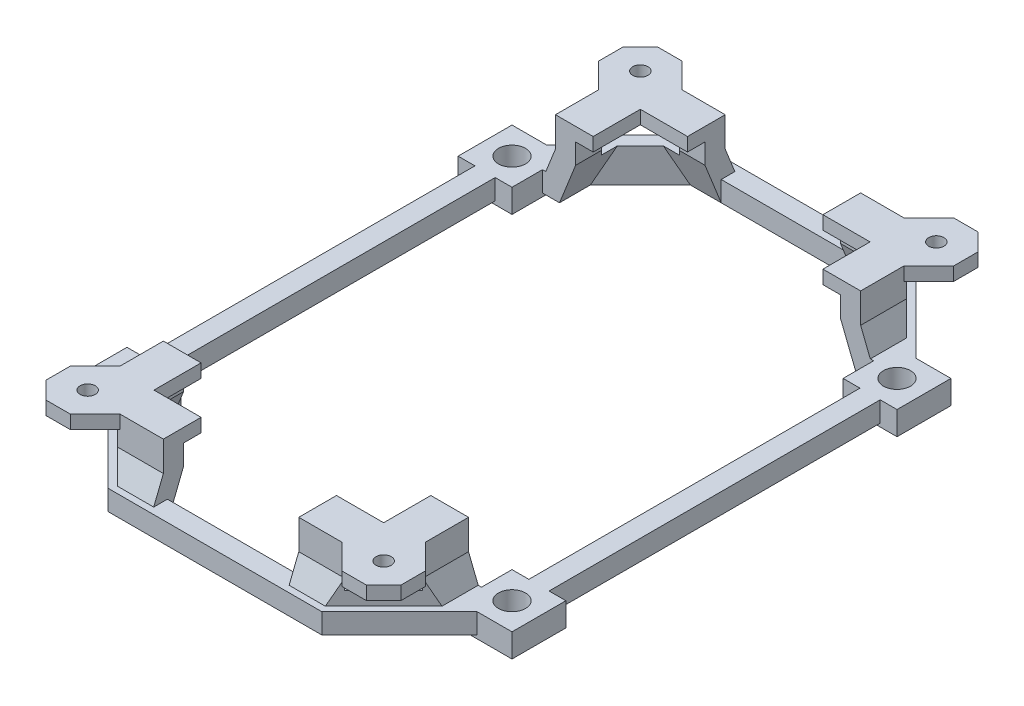
SolidWorks part; units mm, degrees
ref_plane "Front Plane" through (0, 0, 0) normal (0, 0, 1) x (1, 0, 0)
ref_plane "Top Plane" through (0, 0, 0) normal (0, 1, 0) x (1, 0, 0)
ref_plane "Right Plane" through (0, 0, 0) normal (1, 0, 0) x (0, 0, -1)
sketch "Sketch1" plane through (0, 0, 0) normal (0, 1, 0) x (1, 0, 0)
  line L0 (-54.15, 0) -> (-60.15, 0)
  line L1 (-60.15, 0) -> (-60.15, -49.15)
  line L2 (-60.15, -49.15) -> (-65.15, -49.15)
  line L3 (-65.15, -49.15) -> (-65.15, -65.15)
  line L4 (-65.15, -65.15) -> (-54.8069, -65.15)
  line L6 (-54.8069, -65.15) -> (-31.7569, -88.2)
  line L17 (-54.15, 0) -> (-54.15, -49.15)
  line L18 (-54.15, -49.15) -> (-49.15, -49.15)
  line L19 (-49.15, -49.15) -> (-49.15, -58.2)
  line L24 (-54.15, 0) -> (0, 0) construction
  line L25 (0, 0) -> (0, -92.25) construction
  line L26 (-39.3, -58.2) -> (-38.1, -58.2) construction
  line L27 (-38.1, 0) -> (-38.1, -76.2) construction
  line L28 (-65.15, -57.15) -> (-49.15, -57.15) construction
  line L29 (-38.1, -76.2) -> (0, -76.2) construction
  line L37 (-38.1, -76.2) -> (-39.3, -77.4) construction
  line L38 (-39.3, -77.4) -> (-39.3, -58.2) construction
  line L39 (-49.15, -58.2) -> (-39.3, -58.2)
  line L41 (-39.3, -77.4) -> (-20.1, -77.4) construction
  line L42 (-20.1, -77.4) -> (-20.1, -82.2)
  line L44 (-31.7569, -88.2) -> (0, -88.2)
  line L45 (0, -88.2) -> (0, -82.2)
  line L46 (0, -82.2) -> (-20.1, -82.2)
  line L47 (-39.3, -58.2) -> (-39.3, -69.3431)
  line L49 (-31.2431, -77.4) -> (-20.1, -77.4)
  line L50 (-20.1, -77.4) -> (-20.1, -76.2) construction
  line L51 (-39.3, -69.3431) -> (-31.2431, -77.4)
  point P37 (-57.15, 0)
  dimension "D1" = 6
  dimension "D2" = 16
  dimension "D4" = 57.15
  dimension "D5" = 57.15
  dimension "D6" = 76.2
  dimension "D7" = 38.1
  dimension "D8" = 45
  dimension "D10" = 6
  dimension "D9" = 18
  dimension "D3" = 1.2
  dimension "D11" = 135
  dimension "D12" = 4
  dimension "D13" = 4
extrude "Boss-Extrude1" add sketch "Sketch1" along normal blind 6
sketch "Sketch2" plane through (0, 0, 0) normal (0, -1, 0) x (1, 0, 0)
  line L0 (-49.15, 58.2) -> (-49.15, 49.15) construction
  line L1 (-65.15, 49.15) -> (-65.15, 65.15) construction
  line L2 (-49.15, 58.2) -> (-49.15, 49.15)
  line L3 (-65.15, 49.15) -> (-65.15, 65.15)
  line L5 (-65.15, 49.15) -> (-49.15, 49.15)
  line L6 (-65.15, 65.15) -> (-49.15, 65.15)
  line L7 (-49.15, 65.15) -> (-49.15, 58.2)
extrude "Boss-Extrude2" add sketch "Sketch2" along normal blind 1
sketch "Sketch3" plane through (0, 6, 0) normal (0, 1, 0) x (1, 0, 0)
  line L4 (-39.3, -58.2) -> (-45.3, -58.2)
  line L6 (-45.3, -58.2) -> (-45.3, -71.8284)
  line L9 (-20.1, -83.4) -> (-20.1, -77.4)
  line L10 (-45.3, -71.8284) -> (-33.7284, -83.4)
  line L11 (-33.7284, -83.4) -> (-20.1, -83.4)
  line L12 (-54.8069, -65.15) -> (-31.7569, -88.2) construction
  line L13 (-39.3, -58.2) -> (-39.3, -69.3431)
  line L14 (-39.3, -69.3431) -> (-31.2431, -77.4)
  line L15 (-31.2431, -77.4) -> (-20.1, -77.4)
  line L16 (-20.1, -77.4) -> (-31.2431, -77.4) construction
  line L17 (-39.3, -69.3431) -> (-39.3, -58.2) construction
  line L18 (-39.3, -58.2) -> (-49.15, -58.2) construction
  line L19 (-20.1, -82.2) -> (-20.1, -77.4) construction
  line L20 (-39.3, -69.3431) -> (-43.5426, -73.5858) construction
  line L21 (-39.3, -69.3431) -> (-45.3, -69.3431) construction
  dimension "D1" = 6
extrude "Boss-Extrude3" add sketch "Sketch3" along normal blind 12.05
sketch "Sketch4" plane through (0, 18.05, 0) normal (0, 1, 0) x (1, 0, 0)
  line L0 (-45.3, -58.2) -> (-34.1, -58.2)
  line L1 (-34.1, -58.2) -> (-34.1, -72.2)
  line L2 (-34.1, -72.2) -> (-20.1, -72.2)
  line L3 (-20.1, -72.2) -> (-20.1, -83.4)
  line L4 (-20.1, -83.4) -> (-32.9256, -83.4)
  line L5 (-33.7284, -83.4) -> (-20.1, -83.4) construction
  line L6 (-32.9256, -83.4) -> (-40.3093, -90.7836)
  line L7 (-40.3093, -90.7836) -> (-47.558, -90.7836)
  line L8 (-47.558, -90.7836) -> (-52.6836, -85.658)
  line L9 (-52.6836, -85.658) -> (-52.6836, -78.4093)
  line L10 (-52.6836, -78.4093) -> (-45.3, -71.0256)
  line L11 (-45.3, -71.0256) -> (-45.3, -58.2)
  line L12 (-43.9336, -82.0336) -> (-50.1208, -88.2208) construction
  line L13 (-43.9336, -82.0336) -> (-52.6836, -82.0336) construction
  line L14 (-42.3426, -80.4426) -> (-39.5142, -77.6142) construction
  line L15 (-45.3, -71.8284) -> (-33.7284, -83.4) construction
  line L16 (-51.7118, -77.4374) -> (-39.3374, -89.8118) construction
  circle A0 centre (-43.9336, -82.0336) radius 2.25
  dimension "D4" = 4.5
  dimension "D1" = 11.2
  dimension "D2" = 135
  dimension "D3" = 135
  dimension "D6" = 4
  dimension "D5" = 6.5
extrude "Boss-Extrude4" add sketch "Sketch4" along normal blind 4
sketch "Sketch5" plane through (-58.5642, 0, 58.5642) normal (-0.7071, 0, 0.7071) x (0.7071, 0, 0.7071)
  line L0 (18.7584, 18.05) -> (18.7584, 6) construction
  line L1 (18.7584, 18.05) -> (35.1231, 18.05)
  line L2 (18.7584, 18.05) -> (18.7584, 10.05)
  line L3 (18.7584, 10.05) -> (35.1231, 10.05)
  line L4 (35.1231, 18.05) -> (35.1231, 10.05)
  line L5 (35.1231, 18.05) -> (35.1231, 6) construction
  line L6 (18.7584, 18.05) -> (35.1231, 18.05) construction
  dimension "D1" = 8
extrude "Cut-Extrude1" cut sketch "Sketch5" against normal up to next and the other way through all
sketch "Sketch7" plane through (0, 0, 0) normal (0, -1, 0) x (1, 0, 0)
  line L0 (-31.7569, 88.2) -> (-29.2716, 82.2) construction
  line L1 (-29.449, 82.0226) -> (-34.9685, 76.5031) construction
  line L2 (-29.2716, 82.2) -> (0, 82.2) construction
  line L3 (0, 82.2) -> (-20.1, 82.2) construction
  line L4 (-54.8069, 65.15) -> (-31.7569, 88.2) construction
  line L5 (-31.7569, 88.2) -> (0, 88.2) construction
  point P7 (0, 0)
  point P14 (0, 0)
  point P15 (0, 0)
sketch "Sketch6" plane through (-20.1, 0, 0) normal (1, 0, 0) x (0, 0, -1)
  line L1 (-82.2, 0) -> (-77.4, 12.05)
  line L2 (-77.4, 18.05) -> (-77.4, 0) construction
  line L3 (-77.4, 12.05) -> (-77.4, 0)
  line L5 (-77.4, 18.05) -> (-72.2, 18.05) construction
  line L8 (-82.2, 0) -> (-77.4, 0)
  dimension "D1" = 6
extrude "Cut-Extrude2" cut sketch "Sketch6" against normal up to vertex (9.1716 mm away) up to point (-29.2716, 0, 82.2)
ref_plane "Plane1" through (19.05, 0, 19.05) normal (0.7071, 0, 0.7071) x (0.7071, 0, -0.7071)
mirror "Mirror1" about plane through (19.05, 0, 19.05) normal (0.7071, 0, 0.7071) of "Cut-Extrude2"
sketch "Sketch8" plane through (19.05, 0, 19.05) normal (0.7071, 0, 0.7071) x (0.7071, 0, -0.7071)
  line L8 (-78.8223, 0) -> (-78.8223, 10.05)
  line L9 (-78.8223, 10.05) -> (-75.4282, 10.05)
  line L10 (-75.4282, 10.05) -> (-75.4282, 0)
  line L11 (-75.4282, 0) -> (-78.8223, 0)
  line L12 (-75.4282, 0) -> (-75.4282, 10.05) construction
  line L13 (-75.9915, 10.05) -> (-75.4282, 10.05) construction
  point P2 (0, 0)
  point P13 (-76.5193, 8.407)
  point P14 (-75.6586, 9.5342)
  point P15 (-75.8629, 9.3632)
  point P16 (-76.7419, 8.2772)
  point P17 (0, 0)
extrude "Cut-Extrude3" cut sketch "Sketch8" against normal up to surface and the other way up to surface up to face at (-41.1656, 7.3667, 63.9328) other way up to face at (-25.8328, 7.3667, 79.2656)
sketch "Sketch10" plane through (-20.1, 0, 0) normal (1, 0, 0) x (0, 0, -1)
  line L0 (-83.4, 13.201) -> (-86.2685, 6)
  line L1 (-86.2685, 6) -> (-83.4, 6)
  line L2 (-83.4, 6) -> (-83.4, 13.201)
  line L3 (-83.4, 22.05) -> (-83.4, 6) construction
  line L4 (-88.2, 6) -> (-82.2, 6) construction
  line L5 (-77.4, 12.05) -> (-82.2, 0) construction
  line L6 (-78.1967, 10.05) -> (-82.2, 0) construction
  dimension "D1" = 6
extrude "Boss-Extrude5" add sketch "Sketch10" against normal up to vertex (13.6284 mm away)
sketch "Sketch11" plane through (19.05, 0, 19.05) normal (0.7071, 0, 0.7071) x (0.7071, 0, -0.7071)
  line L0 (-82.8223, 13.201) -> (-84.8506, 6)
  line L1 (-84.8506, 6) -> (-82.8223, 6)
  line L2 (-82.8223, 6) -> (-82.8223, 13.201)
  line L3 (-82.8223, 10.05) -> (-82.8223, 6) construction
  line L4 (-84.8223, 6) -> (-82.8223, 6) construction
  line L5 (-82.8223, 13.201) -> (-84.8506, 6) construction
extrude "Cut-Extrude4" cut sketch "Sketch11" along normal through all
mirror "Mirror2" about plane through (19.05, 0, 19.05) normal (0.7071, 0, 0.7071) of "Cut-Extrude4", "Boss-Extrude5"
sketch "Sketch12" plane through (0, 6, 0) normal (0, 1, 0) x (1, 0, 0)
  line L0 (-65.15, -65.15) -> (-49.15, -49.15) construction
  circle A0 centre (-57.15, -57.15) radius 4.0132
  point P6 (0, 0)
  point P7 (-57.15, -57.15)
  dimension "D1" = 8.0264
extrude "Cut-Extrude5" cut sketch "Sketch12" against normal through all
mirror "Mirror3" about plane through (-54.15, 6, 0) normal (0, 0, 1) of bodies 112
mirror "Mirror4" about plane through (0, 6, -88.2) normal (-1, 0, 0) of bodies 113
equation "\"sample_clearance\"= 1.2'sample to edge wall"
equation "\"truss_width\"= 6'thickness"
equation "\"truss_height\"= 6'thickness"
equation "\"truss_offset\"= 1'height offset from baseplate"
equation "\"D1@Sketch1\"=\"truss_width\""
equation "\"screw_spacing_short\"= 4.5in'baseplate spacing parallel to sample short side"
equation "\"screw_spacing_long\"= 4.5in'baseplate spacing parallel to sample long side"
equation "\"truss_bore_width\"= 16'box around bore hole"
equation "\"D2@Sketch1\"=\"truss_bore_width\""
equation "\"D4@Sketch1\"=\"screw_spacing_long\"/2"
equation "\"D5@Sketch1\"=\"screw_spacing_short\"/2"
equation "\"sample_long\"= 6in"
equation "\"sample_short\"= 3in"
equation "\"D6@Sketch1\"=\"sample_long\"/2"
equation "\"D7@Sketch1\"=\"sample_short\"/2"
equation "\"base_clearance_corner\"= 2"
equation "\"wall\"= 12"
equation "\"sample_short_to_truss\"= 6"
equation "\"D10@Sketch1\"=\"sample_short_to_truss\""
equation "\"D1@Boss-Extrude1\"=\"truss_height\""
equation "\"D1@Boss-Extrude2\"=\"truss_offset\""
equation "\"D1@Boss-Extrude3\"=0.75in - \"truss_offset\" - \"truss_height\""
equation "\"D3@Sketch1\"=\"sample_clearance\""
equation "\"D1@Sketch4\"=\"sample_clearance\"+10"
